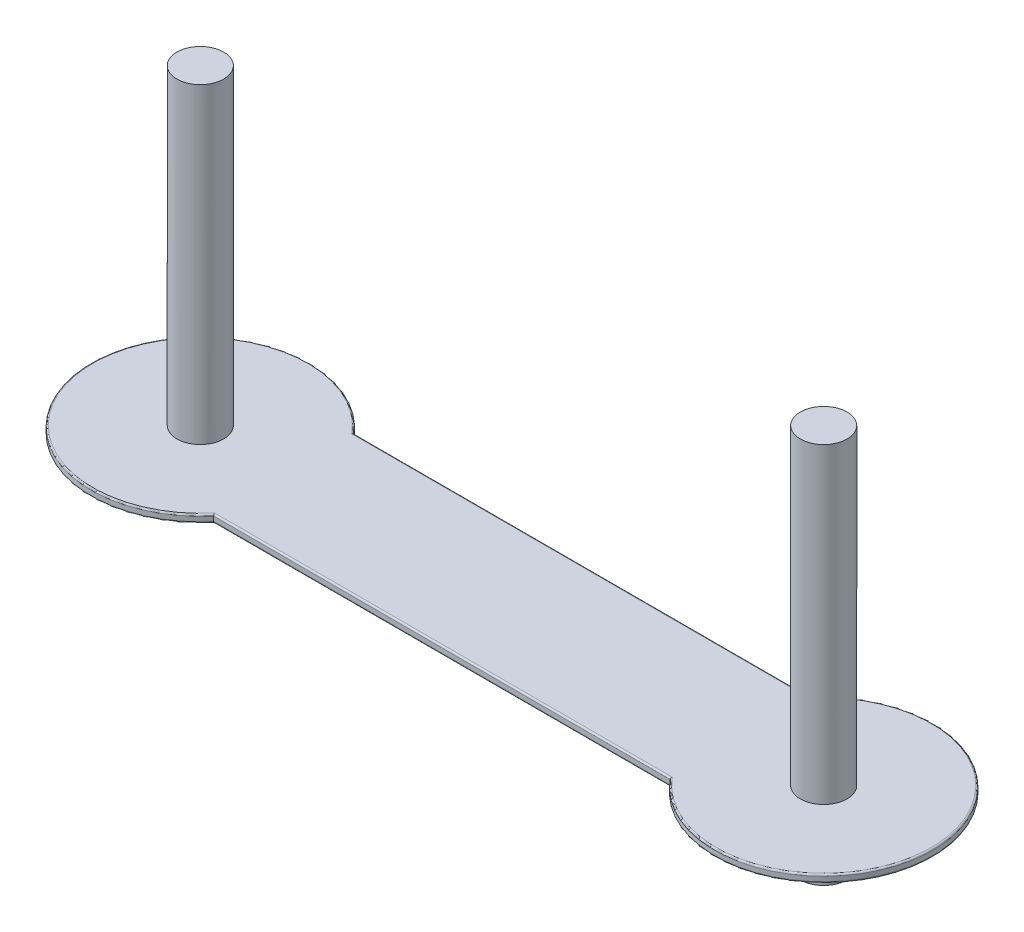
SolidWorks part; units mm, degrees
ref_plane "Front Plane" through (0, 0, 0) normal (0, 0, 1) x (1, 0, 0)
ref_plane "Top Plane" through (0, 0, 0) normal (0, 1, 0) x (1, 0, 0)
ref_plane "Right Plane" through (0, 0, 0) normal (1, 0, 0) x (0, 0, -1)
sketch "Sketch1" plane through (0, 0, 0) normal (0, 1, 0) x (1, 0, 0)
  line L0 (92.9519, 28.575) -> (-92.9519, 28.575)
  line L3 (-92.9519, -28.575) -> (92.9519, -28.575)
  arc A0 (92.9519, -28.575) -> (92.9519, 28.575) centre (127, 0) ccw
  arc A1 (-92.9519, -28.575) -> (-92.9519, 28.575) centre (-127, 0) cw
  point P0 (0, 0)
  dimension "D4" = 44.45
  dimension "D6" = 44.45
  dimension "D1" = 57.15
  dimension "D2" = 28.575
  dimension "D3" = 127
  dimension "D5" = 127
extrude "Boss-Extrude1" add sketch "Sketch1" along normal blind 3.175
sketch "Sketch2" plane through (0, 3.175, 0) normal (0, 1, 0) x (1, 0, 0)
  circle A0 centre (-127, 0) radius 9.525
  circle A1 centre (127, 0) radius 9.525
  dimension "D1" = 19.05
  dimension "D2" = 19.05
extrude "Boss-Extrude2" add sketch "Sketch2" along normal blind 127 contours A0
sketch "Sketch4" plane through (0, 3.175, 0) normal (0, 1, 0) x (1, 0, 0)
  circle A0 centre (127, 0) radius 9.525
  dimension "D1" = 19.05
extrude "Boss-Extrude3" add sketch "Sketch4" along normal blind 127 and the other way blind 28.575
fillet "Fillet3" radius 0.635 8 edges at (0, 3.175, -28.575) (171.45, 3.175, 0) (0, 3.175, 28.575) (-171.45, 3.175, 0) (0, 0, -28.575) (171.45, 0, 0) (0, 0, 28.575) (-171.45, 0, 0)
